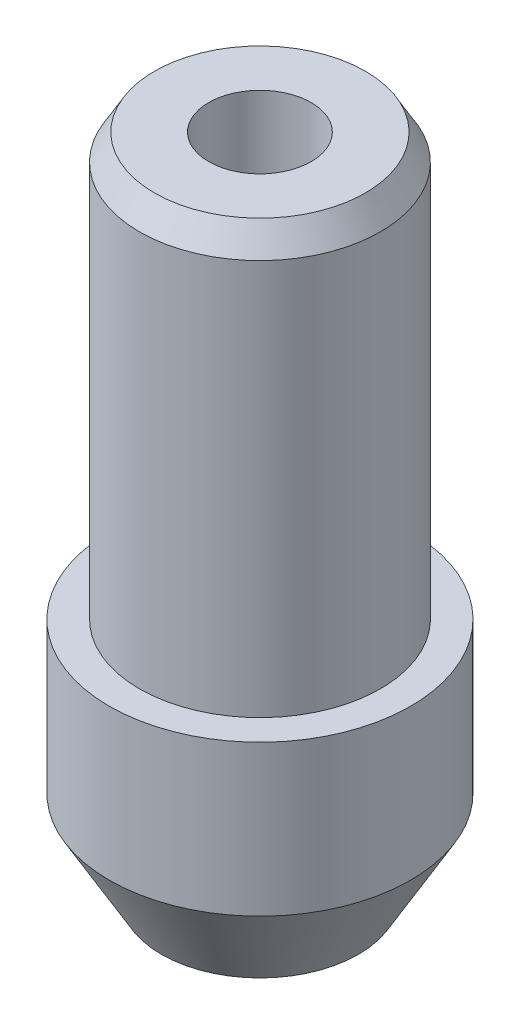
SolidWorks part; units mm, degrees
ref_plane "前视" through (0, 0, 0) normal (0, 0, 1) x (1, 0, 0)
ref_plane "上视" through (0, 0, 0) normal (0, 1, 0) x (1, 0, 0)
ref_plane "右视" through (0, 0, 0) normal (1, 0, 0) x (0, 0, -1)
sketch "草图1" plane through (0, 0, 0) normal (0, 0, 1) x (1, 0, 0)
  line L0 (0, 50.4047) -> (0, -43.684) construction
  line L1 (3.4, 41.0203) -> (7, 41.0203)
  line L2 (7, 41.0203) -> (8, 39.2882)
  line L3 (8, 39.2882) -> (8, 13.0203)
  line L4 (8, 13.0203) -> (10, 13.0203)
  line L5 (10, 13.0203) -> (10, 3.0203)
  line L6 (0, -2.9797) -> (6.5359, -2.9797)
  line L7 (10, 3.0203) -> (6.5359, -2.9797)
  line L8 (0, 24.0573) -> (0, -2.9797)
  line L9 (3.4, 41.0203) -> (3.4, 26.0203)
  line L11 (3.4, 26.0203) -> (0, 24.0573)
  dimension "D1" = 8
  dimension "D2" = 60
  dimension "D3" = 1
  dimension "D4" = 30
  dimension "D5" = 28
  dimension "D6" = 10
  dimension "D7" = 10
  dimension "D8" = 16
  dimension "D9" = 3.4
  dimension "D10" = 15
  dimension "D11" = 60
revolve "基体-旋转" add sketch "草图1" angle 360 about L0
cosmetic thread "装饰螺纹线1"
